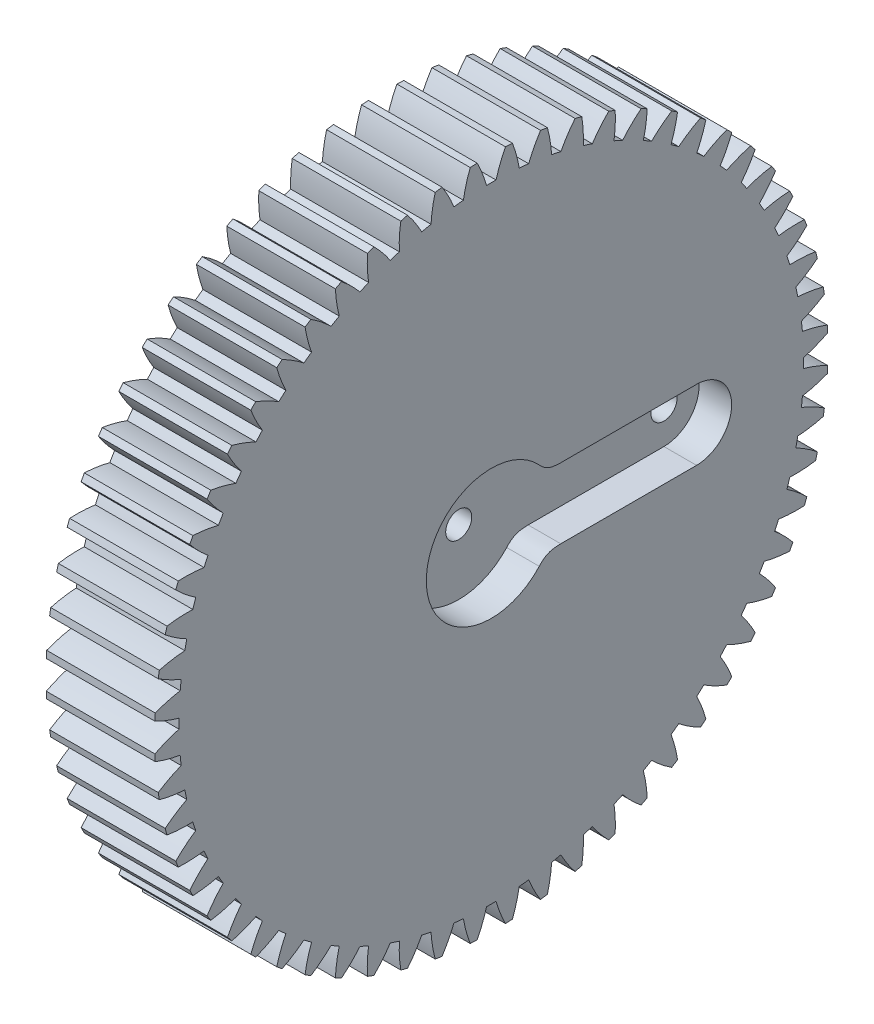
SolidWorks part; units mm, degrees
material "PET"
ref_plane "Front Plane" through (0, 0, 0) normal (0, 0, 1) x (1, 0, 0)
ref_plane "Top Plane" through (0, 0, 0) normal (0, 1, 0) x (1, 0, 0)
ref_plane "Right Plane" through (0, 0, 0) normal (1, 0, 0) x (0, 0, -1)
sketch "Sketch1" plane through (0, 0, 0) normal (1, 0, 0) x (0, 0, -1)
  circle A0 centre (0, 0) radius 3.175
  arc A1 (-39.3352, 1.6555) -> (-36.521, 0.5545) centre (-32.4026, 15.2274) ccw
  arc A2 (-36.521, 0.5545) -> (-36.521, -0.5545) centre (0, 0) ccw
  arc A3 (-36.521, -0.5545) -> (-39.3352, -1.6555) centre (-32.4026, -15.2274) ccw
  arc A4 (-39.3352, -1.6555) -> (-39.2927, -2.4652) centre (0, 0) ccw
  arc A5 (-39.2927, -2.4652) -> (-36.3789, -3.2661) centre (-33.8168, 11.757) ccw
  arc A6 (-36.3789, -3.2661) -> (-36.263, -4.3689) centre (0, 0) ccw
  arc A7 (-36.263, -4.3689) -> (-38.9466, -5.7581) centre (-30.6334, -18.531) ccw
  arc A8 (-38.9466, -5.7581) -> (-38.8198, -6.5589) centre (0, 0) ccw
  arc A9 (-38.8198, -6.5589) -> (-35.8382, -7.0508) centre (-34.8605, 8.1578) ccw
  arc A10 (-35.8382, -7.0508) -> (-35.6076, -8.1355) centre (0, 0) ccw
  arc A11 (-35.6076, -8.1355) -> (-38.1314, -9.7976) centre (-28.5286, -21.6316) ccw
  arc A12 (-38.1314, -9.7976) -> (-37.9216, -10.5808) centre (0, 0) ccw
  arc A13 (-37.9216, -10.5808) -> (-34.9049, -10.7583) centre (-35.5222, 4.4692) ccw
  arc A14 (-34.9049, -10.7583) -> (-34.5622, -11.8129) centre (0, 0) ccw
  arc A15 (-34.5622, -11.8129) -> (-36.8984, -13.7297) centre (-26.1112, -24.4951) ccw
  arc A16 (-36.8984, -13.7297) -> (-36.6078, -14.4867) centre (0, 0) ccw
  arc A17 (-36.6078, -14.4867) -> (-33.5891, -14.3479) centre (-35.7948, 0.7316) ccw
  arc A18 (-33.5891, -14.3479) -> (-33.1381, -15.3609) centre (0, 0) ccw
  arc A19 (-33.1381, -15.3609) -> (-35.2611, -17.5114) centre (-23.4077, -27.0903) ccw
  arc A20 (-35.2611, -17.5114) -> (-34.893, -18.2339) centre (0, 0) ccw
  arc A21 (-34.893, -18.2339) -> (-31.9053, -17.7803) centre (-35.6752, -3.014) ccw
  arc A22 (-31.9053, -17.7803) -> (-31.3509, -18.7407) centre (0, 0) ccw
  arc A23 (-31.3509, -18.7407) -> (-33.2375, -21.1013) centre (-20.4478, -29.3887) ccw
  arc A24 (-33.2375, -21.1013) -> (-32.7959, -21.7813) centre (0, 0) ccw
  arc A25 (-32.7959, -21.7813) -> (-29.872, -21.0179) centre (-35.1647, -6.7265) ccw
  arc A26 (-29.872, -21.0179) -> (-29.2202, -21.9151) centre (0, 0) ccw
  arc A27 (-29.2202, -21.9151) -> (-30.8497, -24.46) centre (-17.2638, -31.365) ccw
  arc A28 (-30.8497, -24.46) -> (-30.3395, -25.0901) centre (0, 0) ccw
  arc A29 (-30.3395, -25.0901) -> (-27.5114, -24.0253) centre (-34.269, -10.3654) ccw
  arc A30 (-27.5114, -24.0253) -> (-26.7694, -24.8494) centre (0, 0) ccw
  arc A31 (-26.7694, -24.8494) -> (-28.124, -27.5507) centre (-13.8907, -32.9978) ccw
  arc A32 (-28.124, -27.5507) -> (-27.5507, -28.124) centre (0, 0) ccw
  arc A33 (-27.5507, -28.124) -> (-24.8494, -26.7694) centre (-32.9978, -13.8907) ccw
  arc A34 (-24.8494, -26.7694) -> (-24.0253, -27.5114) centre (0, 0) ccw
  arc A35 (-24.0253, -27.5114) -> (-25.0901, -30.3395) centre (-10.3654, -34.269) ccw
  arc A36 (-25.0901, -30.3395) -> (-24.46, -30.8497) centre (0, 0) ccw
  arc A37 (-24.46, -30.8497) -> (-21.9151, -29.2202) centre (-31.365, -17.2638) ccw
  arc A38 (-21.9151, -29.2202) -> (-21.0179, -29.872) centre (0, 0) ccw
  arc A39 (-21.0179, -29.872) -> (-21.7813, -32.7959) centre (-6.7265, -35.1647) ccw
  arc A40 (-21.7813, -32.7959) -> (-21.1013, -33.2375) centre (0, 0) ccw
  arc A41 (-21.1013, -33.2375) -> (-18.7407, -31.3509) centre (-29.3887, -20.4478) ccw
  arc A42 (-18.7407, -31.3509) -> (-17.7803, -31.9053) centre (0, 0) ccw
  arc A43 (-17.7803, -31.9053) -> (-18.2339, -34.893) centre (-3.014, -35.6752) ccw
  arc A44 (-18.2339, -34.893) -> (-17.5114, -35.2611) centre (0, 0) ccw
  arc A45 (-17.5114, -35.2611) -> (-15.3609, -33.1381) centre (-27.0903, -23.4077) ccw
  arc A46 (-15.3609, -33.1381) -> (-14.3479, -33.5891) centre (0, 0) ccw
  arc A47 (-14.3479, -33.5891) -> (-14.4867, -36.6078) centre (0.7316, -35.7948) ccw
  arc A48 (-14.4867, -36.6078) -> (-13.7297, -36.8984) centre (0, 0) ccw
  arc A49 (-13.7297, -36.8984) -> (-11.8129, -34.5622) centre (-24.4951, -26.1112) ccw
  arc A50 (-11.8129, -34.5622) -> (-10.7583, -34.9049) centre (0, 0) ccw
  arc A51 (-10.7583, -34.9049) -> (-10.5808, -37.9216) centre (4.4692, -35.5222) ccw
  arc A52 (-10.5808, -37.9216) -> (-9.7976, -38.1314) centre (0, 0) ccw
  arc A53 (-9.7976, -38.1314) -> (-8.1355, -35.6076) centre (-21.6316, -28.5286) ccw
  arc A54 (-8.1355, -35.6076) -> (-7.0508, -35.8382) centre (0, 0) ccw
  arc A55 (-7.0508, -35.8382) -> (-6.5589, -38.8198) centre (8.1578, -34.8605) ccw
  arc A56 (-6.5589, -38.8198) -> (-5.7581, -38.9466) centre (0, 0) ccw
  arc A57 (-5.7581, -38.9466) -> (-4.3689, -36.263) centre (-18.531, -30.6334) ccw
  arc A58 (-4.3689, -36.263) -> (-3.2661, -36.3789) centre (0, 0) ccw
  arc A59 (-3.2661, -36.3789) -> (-2.4652, -39.2927) centre (11.757, -33.8168) ccw
  arc A60 (-2.4652, -39.2927) -> (-1.6555, -39.3352) centre (0, 0) ccw
  arc A61 (-1.6555, -39.3352) -> (-0.5545, -36.521) centre (-15.2274, -32.4026) ccw
  arc A62 (-0.5545, -36.521) -> (0.5545, -36.521) centre (0, 0) ccw
  arc A63 (0.5545, -36.521) -> (1.6555, -39.3352) centre (15.2274, -32.4026) ccw
  arc A64 (1.6555, -39.3352) -> (2.4652, -39.2927) centre (0, 0) ccw
  arc A65 (2.4652, -39.2927) -> (3.2661, -36.3789) centre (-11.757, -33.8168) ccw
  arc A66 (3.2661, -36.3789) -> (4.3689, -36.263) centre (0, 0) ccw
  arc A67 (4.3689, -36.263) -> (5.7581, -38.9466) centre (18.531, -30.6334) ccw
  arc A68 (5.7581, -38.9466) -> (6.5589, -38.8198) centre (0, 0) ccw
  arc A69 (6.5589, -38.8198) -> (7.0508, -35.8382) centre (-8.1578, -34.8605) ccw
  arc A70 (7.0508, -35.8382) -> (8.1355, -35.6076) centre (0, 0) ccw
  arc A71 (8.1355, -35.6076) -> (9.7976, -38.1314) centre (21.6316, -28.5286) ccw
  arc A72 (9.7976, -38.1314) -> (10.5808, -37.9216) centre (0, 0) ccw
  arc A73 (10.5808, -37.9216) -> (10.7583, -34.9049) centre (-4.4692, -35.5222) ccw
  arc A74 (10.7583, -34.9049) -> (11.8129, -34.5622) centre (0, 0) ccw
  arc A75 (11.8129, -34.5622) -> (13.7297, -36.8984) centre (24.4951, -26.1112) ccw
  arc A76 (13.7297, -36.8984) -> (14.4867, -36.6078) centre (0, 0) ccw
  arc A77 (14.4867, -36.6078) -> (14.3479, -33.5891) centre (-0.7316, -35.7948) ccw
  arc A78 (14.3479, -33.5891) -> (15.3609, -33.1381) centre (0, 0) ccw
  arc A79 (15.3609, -33.1381) -> (17.5114, -35.2611) centre (27.0903, -23.4077) ccw
  arc A80 (17.5114, -35.2611) -> (18.2339, -34.893) centre (0, 0) ccw
  arc A81 (18.2339, -34.893) -> (17.7803, -31.9053) centre (3.014, -35.6752) ccw
  arc A82 (17.7803, -31.9053) -> (18.7407, -31.3509) centre (0, 0) ccw
  arc A83 (18.7407, -31.3509) -> (21.1013, -33.2375) centre (29.3887, -20.4478) ccw
  arc A84 (21.1013, -33.2375) -> (21.7813, -32.7959) centre (0, 0) ccw
  arc A85 (21.7813, -32.7959) -> (21.0179, -29.872) centre (6.7265, -35.1647) ccw
  arc A86 (21.0179, -29.872) -> (21.9151, -29.2202) centre (0, 0) ccw
  arc A87 (21.9151, -29.2202) -> (24.46, -30.8497) centre (31.365, -17.2638) ccw
  arc A88 (24.46, -30.8497) -> (25.0901, -30.3395) centre (0, 0) ccw
  arc A89 (25.0901, -30.3395) -> (24.0253, -27.5114) centre (10.3654, -34.269) ccw
  arc A90 (24.0253, -27.5114) -> (24.8494, -26.7694) centre (0, 0) ccw
  arc A91 (24.8494, -26.7694) -> (27.5507, -28.124) centre (32.9978, -13.8907) ccw
  arc A92 (27.5507, -28.124) -> (28.124, -27.5507) centre (0, 0) ccw
  arc A93 (28.124, -27.5507) -> (26.7694, -24.8494) centre (13.8907, -32.9978) ccw
  arc A94 (26.7694, -24.8494) -> (27.5114, -24.0253) centre (0, 0) ccw
  arc A95 (27.5114, -24.0253) -> (30.3395, -25.0901) centre (34.269, -10.3654) ccw
  arc A96 (30.3395, -25.0901) -> (30.8497, -24.46) centre (0, 0) ccw
  arc A97 (30.8497, -24.46) -> (29.2202, -21.9151) centre (17.2638, -31.365) ccw
  arc A98 (29.2202, -21.9151) -> (29.872, -21.0179) centre (0, 0) ccw
  arc A99 (29.872, -21.0179) -> (32.7959, -21.7813) centre (35.1647, -6.7265) ccw
  arc A100 (32.7959, -21.7813) -> (33.2375, -21.1013) centre (0, 0) ccw
  arc A101 (33.2375, -21.1013) -> (31.3509, -18.7407) centre (20.4478, -29.3887) ccw
  arc A102 (31.3509, -18.7407) -> (31.9053, -17.7803) centre (0, 0) ccw
  arc A103 (31.9053, -17.7803) -> (34.893, -18.2339) centre (35.6752, -3.014) ccw
  arc A104 (34.893, -18.2339) -> (35.2611, -17.5114) centre (0, 0) ccw
  arc A105 (35.2611, -17.5114) -> (33.1381, -15.3609) centre (23.4077, -27.0903) ccw
  arc A106 (33.1381, -15.3609) -> (33.5891, -14.3479) centre (0, 0) ccw
  arc A107 (33.5891, -14.3479) -> (36.6078, -14.4867) centre (35.7948, 0.7316) ccw
  arc A108 (36.6078, -14.4867) -> (36.8984, -13.7297) centre (0, 0) ccw
  arc A109 (36.8984, -13.7297) -> (34.5622, -11.8129) centre (26.1112, -24.4951) ccw
  arc A110 (34.5622, -11.8129) -> (34.9049, -10.7583) centre (0, 0) ccw
  arc A111 (34.9049, -10.7583) -> (37.9216, -10.5808) centre (35.5222, 4.4692) ccw
  arc A112 (37.9216, -10.5808) -> (38.1314, -9.7976) centre (0, 0) ccw
  arc A113 (38.1314, -9.7976) -> (35.6076, -8.1355) centre (28.5286, -21.6316) ccw
  arc A114 (35.6076, -8.1355) -> (35.8382, -7.0508) centre (0, 0) ccw
  arc A115 (35.8382, -7.0508) -> (38.8198, -6.5589) centre (34.8605, 8.1578) ccw
  arc A116 (38.8198, -6.5589) -> (38.9466, -5.7581) centre (0, 0) ccw
  arc A117 (38.9466, -5.7581) -> (36.263, -4.3689) centre (30.6334, -18.531) ccw
  arc A118 (36.263, -4.3689) -> (36.3789, -3.2661) centre (0, 0) ccw
  arc A119 (36.3789, -3.2661) -> (39.2927, -2.4652) centre (33.8168, 11.757) ccw
  arc A120 (39.2927, -2.4652) -> (39.3352, -1.6555) centre (0, 0) ccw
  arc A121 (39.3352, -1.6555) -> (36.521, -0.5545) centre (32.4026, -15.2274) ccw
  arc A122 (36.521, -0.5545) -> (36.521, 0.5545) centre (0, 0) ccw
  arc A123 (36.521, 0.5545) -> (39.3352, 1.6555) centre (32.4026, 15.2274) ccw
  arc A124 (39.3352, 1.6555) -> (39.2927, 2.4652) centre (0, 0) ccw
  arc A125 (39.2927, 2.4652) -> (36.3789, 3.2661) centre (33.8168, -11.757) ccw
  arc A126 (36.3789, 3.2661) -> (36.263, 4.3689) centre (0, 0) ccw
  arc A127 (36.263, 4.3689) -> (38.9466, 5.7581) centre (30.6334, 18.531) ccw
  arc A128 (38.9466, 5.7581) -> (38.8198, 6.5589) centre (0, 0) ccw
  arc A129 (38.8198, 6.5589) -> (35.8382, 7.0508) centre (34.8605, -8.1578) ccw
  arc A130 (35.8382, 7.0508) -> (35.6076, 8.1355) centre (0, 0) ccw
  arc A131 (35.6076, 8.1355) -> (38.1314, 9.7976) centre (28.5286, 21.6316) ccw
  arc A132 (38.1314, 9.7976) -> (37.9216, 10.5808) centre (0, 0) ccw
  arc A133 (37.9216, 10.5808) -> (34.9049, 10.7583) centre (35.5222, -4.4692) ccw
  arc A134 (34.9049, 10.7583) -> (34.5622, 11.8129) centre (0, 0) ccw
  arc A135 (34.5622, 11.8129) -> (36.8984, 13.7297) centre (26.1112, 24.4951) ccw
  arc A136 (36.8984, 13.7297) -> (36.6078, 14.4867) centre (0, 0) ccw
  arc A137 (36.6078, 14.4867) -> (33.5891, 14.3479) centre (35.7948, -0.7316) ccw
  arc A138 (33.5891, 14.3479) -> (33.1381, 15.3609) centre (0, 0) ccw
  arc A139 (33.1381, 15.3609) -> (35.2611, 17.5114) centre (23.4077, 27.0903) ccw
  arc A140 (35.2611, 17.5114) -> (34.893, 18.2339) centre (0, 0) ccw
  arc A141 (34.893, 18.2339) -> (31.9053, 17.7803) centre (35.6752, 3.014) ccw
  arc A142 (31.9053, 17.7803) -> (31.3509, 18.7407) centre (0, 0) ccw
  arc A143 (31.3509, 18.7407) -> (33.2375, 21.1013) centre (20.4478, 29.3887) ccw
  arc A144 (33.2375, 21.1013) -> (32.7959, 21.7813) centre (0, 0) ccw
  arc A145 (32.7959, 21.7813) -> (29.872, 21.0179) centre (35.1647, 6.7265) ccw
  arc A146 (29.872, 21.0179) -> (29.2202, 21.9151) centre (0, 0) ccw
  arc A147 (29.2202, 21.9151) -> (30.8497, 24.46) centre (17.2638, 31.365) ccw
  arc A148 (30.8497, 24.46) -> (30.3395, 25.0901) centre (0, 0) ccw
  arc A149 (30.3395, 25.0901) -> (27.5114, 24.0253) centre (34.269, 10.3654) ccw
  arc A150 (27.5114, 24.0253) -> (26.7694, 24.8494) centre (0, 0) ccw
  arc A151 (26.7694, 24.8494) -> (28.124, 27.5507) centre (13.8907, 32.9978) ccw
  arc A152 (28.124, 27.5507) -> (27.5507, 28.124) centre (0, 0) ccw
  arc A153 (27.5507, 28.124) -> (24.8494, 26.7694) centre (32.9978, 13.8907) ccw
  arc A154 (24.8494, 26.7694) -> (24.0253, 27.5114) centre (0, 0) ccw
  arc A155 (24.0253, 27.5114) -> (25.0901, 30.3395) centre (10.3654, 34.269) ccw
  arc A156 (25.0901, 30.3395) -> (24.46, 30.8497) centre (0, 0) ccw
  arc A157 (24.46, 30.8497) -> (21.9151, 29.2202) centre (31.365, 17.2638) ccw
  arc A158 (21.9151, 29.2202) -> (21.0179, 29.872) centre (0, 0) ccw
  arc A159 (21.0179, 29.872) -> (21.7813, 32.7959) centre (6.7265, 35.1647) ccw
  arc A160 (21.7813, 32.7959) -> (21.1013, 33.2375) centre (0, 0) ccw
  arc A161 (21.1013, 33.2375) -> (18.7407, 31.3509) centre (29.3887, 20.4478) ccw
  arc A162 (18.7407, 31.3509) -> (17.7803, 31.9053) centre (0, 0) ccw
  arc A163 (17.7803, 31.9053) -> (18.2339, 34.893) centre (3.014, 35.6752) ccw
  arc A164 (18.2339, 34.893) -> (17.5114, 35.2611) centre (0, 0) ccw
  arc A165 (17.5114, 35.2611) -> (15.3609, 33.1381) centre (27.0903, 23.4077) ccw
  arc A166 (15.3609, 33.1381) -> (14.3479, 33.5891) centre (0, 0) ccw
  arc A167 (14.3479, 33.5891) -> (14.4867, 36.6078) centre (-0.7316, 35.7948) ccw
  arc A168 (14.4867, 36.6078) -> (13.7297, 36.8984) centre (0, 0) ccw
  arc A169 (13.7297, 36.8984) -> (11.8129, 34.5622) centre (24.4951, 26.1112) ccw
  arc A170 (11.8129, 34.5622) -> (10.7583, 34.9049) centre (0, 0) ccw
  arc A171 (10.7583, 34.9049) -> (10.5808, 37.9216) centre (-4.4692, 35.5222) ccw
  arc A172 (10.5808, 37.9216) -> (9.7976, 38.1314) centre (0, 0) ccw
  arc A173 (9.7976, 38.1314) -> (8.1355, 35.6076) centre (21.6316, 28.5286) ccw
  arc A174 (8.1355, 35.6076) -> (7.0508, 35.8382) centre (0, 0) ccw
  arc A175 (7.0508, 35.8382) -> (6.5589, 38.8198) centre (-8.1578, 34.8605) ccw
  arc A176 (6.5589, 38.8198) -> (5.7581, 38.9466) centre (0, 0) ccw
  arc A177 (5.7581, 38.9466) -> (4.3689, 36.263) centre (18.531, 30.6334) ccw
  arc A178 (4.3689, 36.263) -> (3.2661, 36.3789) centre (0, 0) ccw
  arc A179 (3.2661, 36.3789) -> (2.4652, 39.2927) centre (-11.757, 33.8168) ccw
  arc A180 (2.4652, 39.2927) -> (1.6555, 39.3352) centre (0, 0) ccw
  arc A181 (1.6555, 39.3352) -> (0.5545, 36.521) centre (15.2274, 32.4026) ccw
  arc A182 (0.5545, 36.521) -> (-0.5545, 36.521) centre (0, 0) ccw
  arc A183 (-0.5545, 36.521) -> (-1.6555, 39.3352) centre (-15.2274, 32.4026) ccw
  arc A184 (-1.6555, 39.3352) -> (-2.4652, 39.2927) centre (0, 0) ccw
  arc A185 (-2.4652, 39.2927) -> (-3.2661, 36.3789) centre (11.757, 33.8168) ccw
  arc A186 (-3.2661, 36.3789) -> (-4.3689, 36.263) centre (0, 0) ccw
  arc A187 (-4.3689, 36.263) -> (-5.7581, 38.9466) centre (-18.531, 30.6334) ccw
  arc A188 (-5.7581, 38.9466) -> (-6.5589, 38.8198) centre (0, 0) ccw
  arc A189 (-6.5589, 38.8198) -> (-7.0508, 35.8382) centre (8.1578, 34.8605) ccw
  arc A190 (-7.0508, 35.8382) -> (-8.1355, 35.6076) centre (0, 0) ccw
  arc A191 (-8.1355, 35.6076) -> (-9.7976, 38.1314) centre (-21.6316, 28.5286) ccw
  arc A192 (-9.7976, 38.1314) -> (-10.5808, 37.9216) centre (0, 0) ccw
  arc A193 (-10.5808, 37.9216) -> (-10.7583, 34.9049) centre (4.4692, 35.5222) ccw
  arc A194 (-10.7583, 34.9049) -> (-11.8129, 34.5622) centre (0, 0) ccw
  arc A195 (-11.8129, 34.5622) -> (-13.7297, 36.8984) centre (-24.4951, 26.1112) ccw
  arc A196 (-13.7297, 36.8984) -> (-14.4867, 36.6078) centre (0, 0) ccw
  arc A197 (-14.4867, 36.6078) -> (-14.3479, 33.5891) centre (0.7316, 35.7948) ccw
  arc A198 (-14.3479, 33.5891) -> (-15.3609, 33.1381) centre (0, 0) ccw
  arc A199 (-15.3609, 33.1381) -> (-17.5114, 35.2611) centre (-27.0903, 23.4077) ccw
  arc A200 (-17.5114, 35.2611) -> (-18.2339, 34.893) centre (0, 0) ccw
  arc A201 (-18.2339, 34.893) -> (-17.7803, 31.9053) centre (-3.014, 35.6752) ccw
  arc A202 (-17.7803, 31.9053) -> (-18.7407, 31.3509) centre (0, 0) ccw
  arc A203 (-18.7407, 31.3509) -> (-21.1013, 33.2375) centre (-29.3887, 20.4478) ccw
  arc A204 (-21.1013, 33.2375) -> (-21.7813, 32.7959) centre (0, 0) ccw
  arc A205 (-21.7813, 32.7959) -> (-21.0179, 29.872) centre (-6.7265, 35.1647) ccw
  arc A206 (-21.0179, 29.872) -> (-21.9151, 29.2202) centre (0, 0) ccw
  arc A207 (-21.9151, 29.2202) -> (-24.46, 30.8497) centre (-31.365, 17.2638) ccw
  arc A208 (-24.46, 30.8497) -> (-25.0901, 30.3395) centre (0, 0) ccw
  arc A209 (-25.0901, 30.3395) -> (-24.0253, 27.5114) centre (-10.3654, 34.269) ccw
  arc A210 (-24.0253, 27.5114) -> (-24.8494, 26.7694) centre (0, 0) ccw
  arc A211 (-24.8494, 26.7694) -> (-27.5507, 28.124) centre (-32.9978, 13.8907) ccw
  arc A212 (-27.5507, 28.124) -> (-28.124, 27.5507) centre (0, 0) ccw
  arc A213 (-28.124, 27.5507) -> (-26.7694, 24.8494) centre (-13.8907, 32.9978) ccw
  arc A214 (-26.7694, 24.8494) -> (-27.5114, 24.0253) centre (0, 0) ccw
  arc A215 (-27.5114, 24.0253) -> (-30.3395, 25.0901) centre (-34.269, 10.3654) ccw
  arc A216 (-30.3395, 25.0901) -> (-30.8497, 24.46) centre (0, 0) ccw
  arc A217 (-30.8497, 24.46) -> (-29.2202, 21.9151) centre (-17.2638, 31.365) ccw
  arc A218 (-29.2202, 21.9151) -> (-29.872, 21.0179) centre (0, 0) ccw
  arc A219 (-29.872, 21.0179) -> (-32.7959, 21.7813) centre (-35.1647, 6.7265) ccw
  arc A220 (-32.7959, 21.7813) -> (-33.2375, 21.1013) centre (0, 0) ccw
  arc A221 (-33.2375, 21.1013) -> (-31.3509, 18.7407) centre (-20.4478, 29.3887) ccw
  arc A222 (-31.3509, 18.7407) -> (-31.9053, 17.7803) centre (0, 0) ccw
  arc A223 (-31.9053, 17.7803) -> (-34.893, 18.2339) centre (-35.6752, 3.014) ccw
  arc A224 (-34.893, 18.2339) -> (-35.2611, 17.5114) centre (0, 0) ccw
  arc A225 (-35.2611, 17.5114) -> (-33.1381, 15.3609) centre (-23.4077, 27.0903) ccw
  arc A226 (-33.1381, 15.3609) -> (-33.5891, 14.3479) centre (0, 0) ccw
  arc A227 (-33.5891, 14.3479) -> (-36.6078, 14.4867) centre (-35.7948, -0.7316) ccw
  arc A228 (-36.6078, 14.4867) -> (-36.8984, 13.7297) centre (0, 0) ccw
  arc A229 (-36.8984, 13.7297) -> (-34.5622, 11.8129) centre (-26.1112, 24.4951) ccw
  arc A230 (-34.5622, 11.8129) -> (-34.9049, 10.7583) centre (0, 0) ccw
  arc A231 (-34.9049, 10.7583) -> (-37.9216, 10.5808) centre (-35.5222, -4.4692) ccw
  arc A232 (-37.9216, 10.5808) -> (-38.1314, 9.7976) centre (0, 0) ccw
  arc A233 (-38.1314, 9.7976) -> (-35.6076, 8.1355) centre (-28.5286, 21.6316) ccw
  arc A234 (-35.6076, 8.1355) -> (-35.8382, 7.0508) centre (0, 0) ccw
  arc A235 (-35.8382, 7.0508) -> (-38.8198, 6.5589) centre (-34.8605, -8.1578) ccw
  arc A236 (-38.8198, 6.5589) -> (-38.9466, 5.7581) centre (0, 0) ccw
  arc A237 (-38.9466, 5.7581) -> (-36.263, 4.3689) centre (-30.6334, 18.531) ccw
  arc A238 (-36.263, 4.3689) -> (-36.3789, 3.2661) centre (0, 0) ccw
  arc A239 (-36.3789, 3.2661) -> (-39.2927, 2.4652) centre (-33.8168, -11.757) ccw
  arc A240 (-39.2927, 2.4652) -> (-39.3352, 1.6555) centre (0, 0) ccw
extrude "Boss-Extrude1" add sketch "Sketch1" against normal blind 12.7
sketch "Sketch3" plane through (0, 0, 0) normal (-1, 0, 0) x (0, 0, 1)
  line L0 (-24, 4.1016) -> (-8.1182, 4.1016)
  line L1 (-24, -4.1016) -> (-8.1182, -4.1016)
  line L2 (0, 0) -> (-24.1398, 0) construction
  arc A288 (-5.6095, -5.1301) -> (-5.6095, 5.1301) centre (0, 0) ccw
  arc A290 (-24, 4.1016) -> (-24, -4.1016) centre (-24, 0) ccw
  spline S0 degree 3 poles (-5.6095, 5.1301) (-6.5804, 4.03) (-7.4218, 4.1671) (-8.1182, 4.1016) knots 0 0 0 0 1 1 1 1
  spline S1 degree 3 poles (-5.6095, -5.1301) (-6.5804, -4.03) (-7.4218, -4.1671) (-8.1182, -4.1016) knots 0 0 0 0 1 1 1 1
extrude "Cut-Extrude1" cut sketch "Sketch3" along normal blind 3.81
sketch "Sketch4" plane through (-3.81, 0, 0) normal (1, 0, 0) x (0, 0, -1)
  circle A0 centre (24, 0) radius 1.524
  dimension "D1" = 3.048
extrude "Cut-Extrude2" cut sketch "Sketch4" against normal through all
sketch "Sketch5" plane through (-12.7, 0, 0) normal (-1, 0, 0) x (0, 0, 1)
  circle A0 centre (-24, 0) radius 3.175
  dimension "D1" = 6.35
extrude "Cut-Extrude3" cut sketch "Sketch5" against normal blind 2.54
sketch "Sketch6" plane through (-12.7, 0, 0) normal (-1, 0, 0) x (0, 0, 1)
  circle A0 centre (0, 0) radius 1.524
  circle A1 centre (0, 0) radius 3.175
  circle A2 centre (0, 0) radius 3.175 construction
  dimension "D1" = 3.048
extrude "Boss-Extrude2" add sketch "Sketch6" against normal up to surface (6.35 mm away) from surface at -2.54 up to face at (-3.81, 0, -25.524) starting at face at (-10.16, 0, -20.825)
